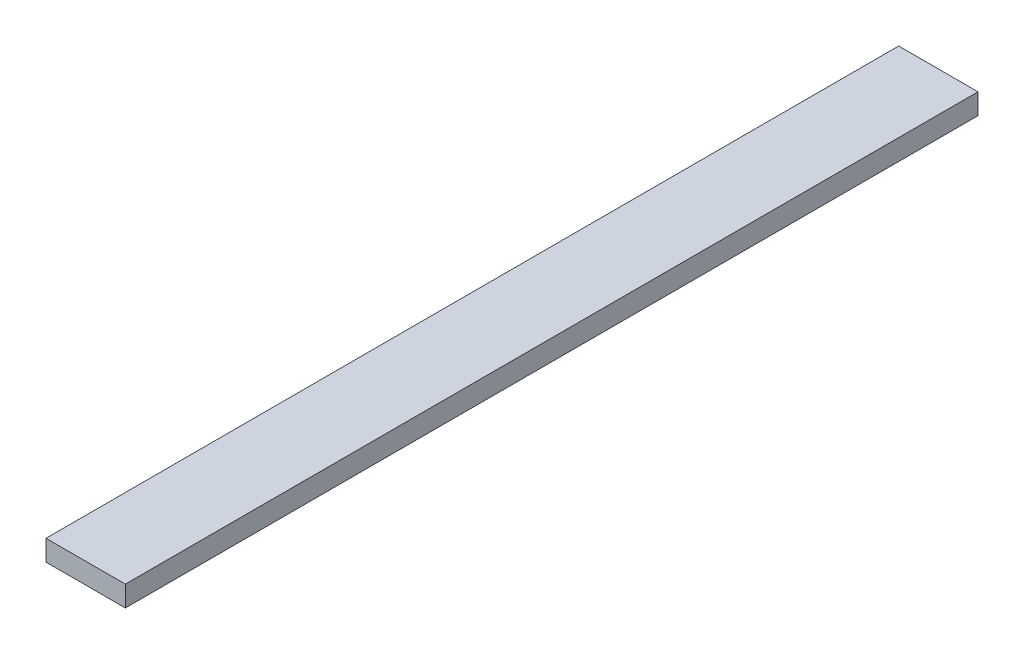
SolidWorks part; units mm, degrees
material "Acrylic (Medium-high impact)"
ref_plane "Front" through (0, 0, 0) normal (0, 0, 1) x (1, 0, 0)
ref_plane "Top" through (0, 0, 0) normal (0, 1, 0) x (1, 0, 0)
ref_plane "Right" through (0, 0, 0) normal (1, 0, 0) x (0, 0, -1)
sketch "Sketch1" plane through (0, 0, 0) normal (0, 1, 0) x (1, 0, 0)
  line L1 (0, -130.823) -> (24.346, -130.823)
  line L2 (0, -130.823) -> (0, 130.823)
  line L3 (0, 130.823) -> (24.346, 130.823)
  line L4 (24.346, -130.823) -> (24.346, 130.823)
  point P6 (0, 0)
  dimension "D1" = 261.646
  dimension "D2" = 24.346
extrude "Boss-Extrude1" add sketch "Sketch1" along normal blind 6.35
other "PropertyManager" [suppressed]
equation "\"thick\"= .25in"
equation "\"tol\"= .005in"
equation "\"ftprnt\"= 30cm"
equation "\"D1@Sketch1\"=\"ftprnt\"-(\"thick\"*6)-(\"tol\"*2)"
equation "\"D1@Boss-Extrude1\"=\"thick\""
equation "\"height\"= 5cm"
equation "\"D2@Sketch1\"=\"height\"-(4*\"thick\")-(2*\"tol\")"
